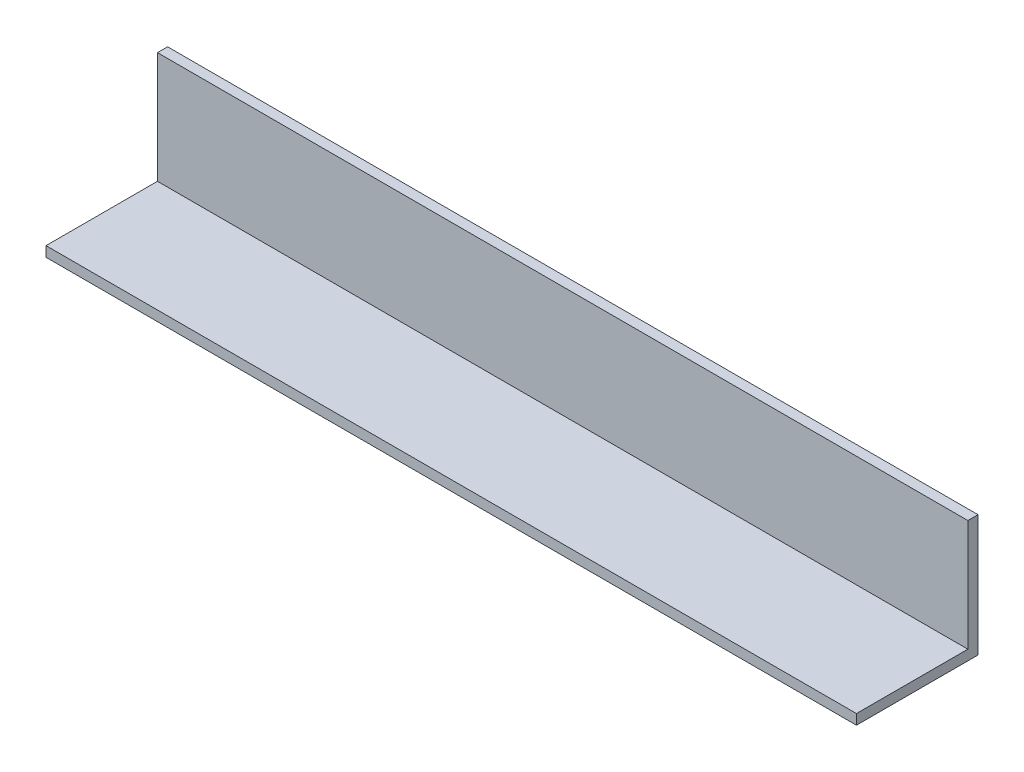
SolidWorks part; units mm, degrees
ref_plane "Front Plane" through (0, 0, 0) normal (0, 0, 1) x (1, 0, 0)
ref_plane "Top Plane" through (0, 0, 0) normal (0, 1, 0) x (1, 0, 0)
ref_plane "Right Plane" through (0, 0, 0) normal (1, 0, 0) x (0, 0, -1)
sketch "Sketch2" plane through (0, 0, 0) normal (1, 0, 0) x (0, 0, -1)
  line L1 (0, 0) -> (19.05, 0)
  line L2 (0, 0) -> (0, 19.05)
  line L3 (0, 19.05) -> (19.05, 19.05)
  line L4 (19.05, 0) -> (19.05, 19.05)
  dimension "D1" = 19.05
  dimension "D2" = 19.05
extrude "Boss-Extrude1" add sketch "Sketch2" along normal blind 127
sketch "Sketch4" plane through (0, 0, 0) normal (-1, 0, 0) x (0, 0, 1)
  line L1 (0, 19.05) -> (-17.4625, 19.05)
  line L2 (0, 19.05) -> (0, 1.5875)
  line L3 (0, 1.5875) -> (-17.4625, 1.5875)
  line L4 (-17.4625, 19.05) -> (-17.4625, 1.5875)
  dimension "D1" = 17.4625
  dimension "D2" = 17.4625
extrude "Cut-Extrude1" cut sketch "Sketch4" against normal blind 127
